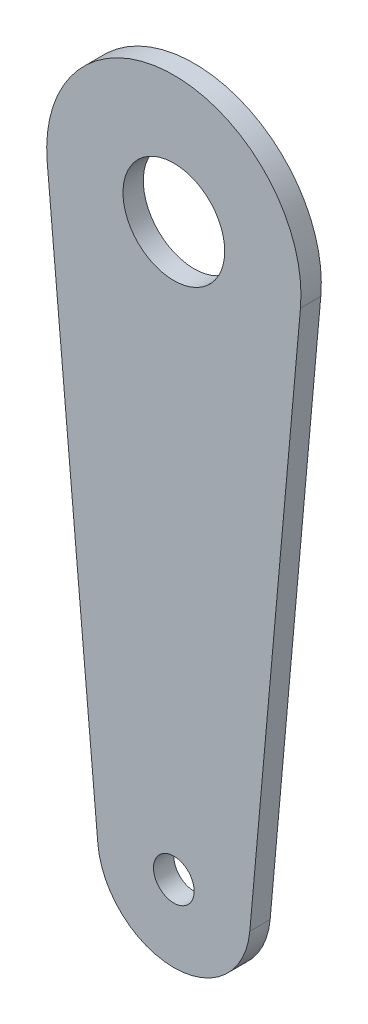
SolidWorks part; units mm, degrees
material "PLA"
ref_plane "Alzado" through (0, 0, 0) normal (0, 0, 1) x (1, 0, 0)
ref_plane "Planta" through (0, 0, 0) normal (0, 1, 0) x (1, 0, 0)
ref_plane "Vista lateral" through (0, 0, 0) normal (1, 0, 0) x (0, 0, -1)
other "PLA"
sketch "Croquis1" plane through (0, 0, 0) normal (0, 0, 1) x (1, 0, 0)
  line L0 (0, 100.425) -> (0, -11.575) construction
  line L1 (-14.9401, -12.9143) -> (-25.1002, 100.425)
  line L2 (14.9401, -12.9143) -> (24.9002, 98.1929)
  arc A0 (-14.9401, -12.9143) -> (14.9401, -12.9143) centre (0, -11.575) ccw
  arc A1 (24.9002, 98.1929) -> (-24.9002, 98.1929) centre (0, 100.425) ccw
  circle A2 centre (0, 100.425) radius 10
  circle A3 centre (0, -11.575) radius 4
  dimension "D1" = 30
  dimension "D2" = 50
  dimension "D4" = 20
  dimension "D5" = 8
  dimension "D3" = 112
extrude "Saliente-Extruir1" add sketch "Croquis1" along normal blind 4
